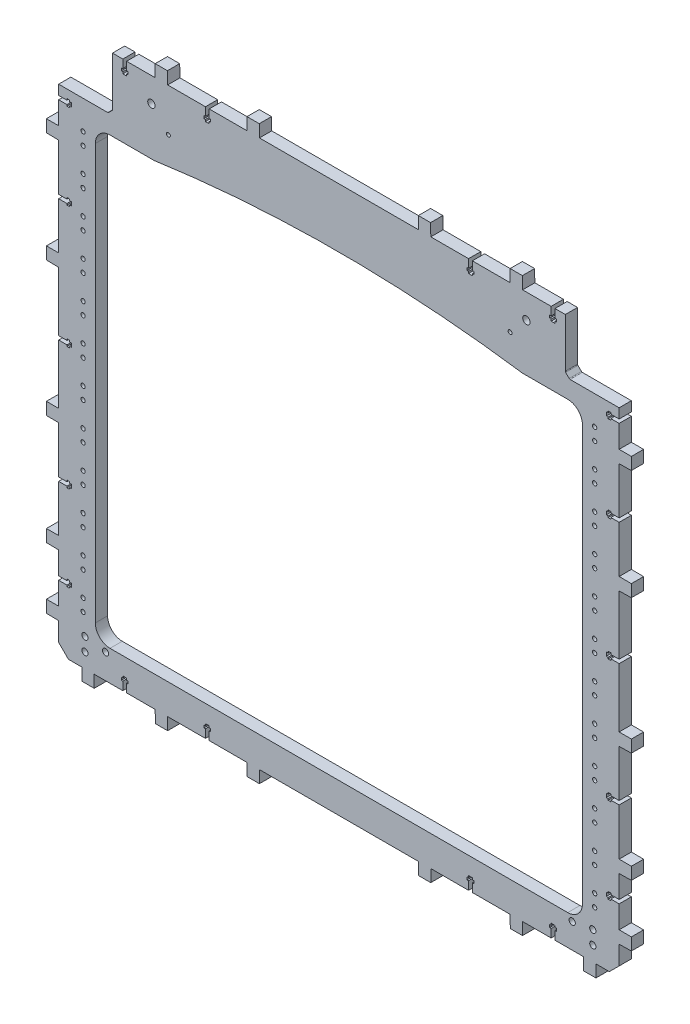
SolidWorks part; units mm, degrees
ref_plane "Front" through (0, 0, 0) normal (0, 0, 1) x (1, 0, 0)
ref_plane "Top" through (0, 0, 0) normal (0, 1, 0) x (1, 0, 0)
ref_plane "Right" through (0, 0, 0) normal (1, 0, 0) x (0, 0, -1)
sketch "Эскиз1" plane through (0, 0, 0) normal (0, 0, 1) x (1, 0, 0)
  line L0 (-199, -186.7207) -> (-199, 152.5)
  line L1 (109.05, 213) -> (105.95, 213)
  line L2 (186.9993, -198.7207) -> (-187, -198.7207)
  line L3 (199, 152.5) -> (198.9993, -186.7207)
  line L4 (109.05, 214.5) -> (109.05, 213)
  line L5 (110.25, 214.5) -> (109.05, 214.5)
  line L6 (110.25, 216.7) -> (110.25, 214.5)
  line L7 (109.05, 216.7) -> (110.25, 216.7)
  line L8 (109.05, 223.5) -> (109.05, 216.7)
  line L9 (139.9, 223.5) -> (109.05, 223.5)
  line L10 (139.9334, 233.4986) -> (139.9, 223.5)
  line L11 (149.9334, 233.4986) -> (139.9334, 233.4986)
  line L12 (150.1, 223.5) -> (149.9334, 233.4986)
  line L13 (173.45, 223.5) -> (150.1, 223.5)
  line L14 (173.45, 216.7) -> (173.45, 223.5)
  line L15 (172.25, 216.7) -> (173.45, 216.7)
  line L16 (172.25, 214.5) -> (172.25, 216.7)
  line L17 (173.45, 214.5) -> (172.25, 214.5)
  line L18 (173.45, 213) -> (173.45, 214.5)
  line L19 (176.55, 213) -> (173.45, 213)
  line L20 (176.55, 214.5) -> (176.55, 213)
  line L21 (177.75, 214.5) -> (176.55, 214.5)
  line L22 (177.75, 216.7) -> (177.75, 214.5)
  line L23 (176.55, 216.7) -> (177.75, 216.7)
  line L24 (176.55, 223.5) -> (176.55, 216.7)
  line L25 (185, 223.5) -> (176.55, 223.5)
  line L26 (229, 171.55) -> (229, 179.5)
  line L27 (222.2, 171.55) -> (229, 171.55)
  line L28 (222.2, 172.75) -> (222.2, 171.55)
  line L29 (220, 172.75) -> (222.2, 172.75)
  line L30 (220, 171.55) -> (220, 172.75)
  line L31 (218.5, 171.55) -> (220, 171.55)
  line L32 (218.5, 168.45) -> (218.5, 171.55)
  line L33 (220, 168.45) -> (218.5, 168.45)
  line L34 (220, 167.25) -> (220, 168.45)
  line L35 (222.2, 167.25) -> (220, 167.25)
  line L36 (222.2, 168.45) -> (222.2, 167.25)
  line L37 (229, 168.45) -> (222.2, 168.45)
  line L38 (229, 150.1) -> (229, 168.45)
  line L39 (238.9986, 150.0666) -> (229, 150.1)
  line L40 (238.9986, 140.0666) -> (238.9986, 150.0666)
  line L41 (229, 139.9) -> (238.9986, 140.0666)
  line L42 (229, 101.55) -> (229, 139.9)
  line L43 (222.2, 101.55) -> (229, 101.55)
  line L44 (222.2, 102.75) -> (222.2, 101.55)
  line L45 (220, 102.75) -> (222.2, 102.75)
  line L46 (220, 101.55) -> (220, 102.75)
  line L47 (218.5, 101.55) -> (220, 101.55)
  line L48 (218.5, 98.45) -> (218.5, 101.55)
  line L49 (220, 98.45) -> (218.5, 98.45)
  line L50 (220, 97.25) -> (220, 98.45)
  line L51 (222.2, 97.25) -> (220, 97.25)
  line L52 (222.2, 98.45) -> (222.2, 97.25)
  line L53 (229, 98.45) -> (222.2, 98.45)
  line L54 (229, 60.1) -> (229, 98.45)
  line L55 (238.9986, 60.0666) -> (229, 60.1)
  line L56 (238.9986, 50.0666) -> (238.9986, 60.0666)
  line L57 (229, 49.9) -> (238.9986, 50.0666)
  line L58 (238.9986, -49.9334) -> (229, -49.9)
  line L59 (238.9986, -59.9334) -> (238.9986, -49.9334)
  line L60 (229, -60.1) -> (238.9986, -59.9334)
  line L61 (229, -98.45) -> (229, -60.1)
  line L62 (222.2, -98.45) -> (229, -98.45)
  line L63 (222.2, -97.25) -> (222.2, -98.45)
  line L64 (220, -97.25) -> (222.2, -97.25)
  line L65 (220, -98.45) -> (220, -97.25)
  line L66 (218.5, -98.45) -> (220, -98.45)
  line L67 (218.5, -101.55) -> (218.5, -98.45)
  line L68 (220, -101.55) -> (218.5, -101.55)
  line L69 (220, -102.75) -> (220, -101.55)
  line L70 (222.2, -102.75) -> (220, -102.75)
  line L71 (222.2, -101.55) -> (222.2, -102.75)
  line L72 (229, -101.55) -> (222.2, -101.55)
  line L73 (229, -139.9) -> (229, -101.55)
  line L74 (238.9986, -139.9334) -> (229, -139.9)
  line L75 (238.9986, -149.9334) -> (238.9986, -139.9334)
  line L76 (229, -150.1) -> (238.9986, -149.9334)
  line L77 (229, -168.45) -> (229, -150.1)
  line L78 (222.2, -168.45) -> (229, -168.45)
  line L79 (222.2, -167.25) -> (222.2, -168.45)
  line L80 (220, -167.25) -> (222.2, -167.25)
  line L81 (220, -168.45) -> (220, -167.25)
  line L82 (218.5, -168.45) -> (220, -168.45)
  line L83 (218.5, -171.55) -> (218.5, -168.45)
  line L84 (220, -171.55) -> (218.5, -171.55)
  line L85 (220, -172.75) -> (220, -171.55)
  line L86 (222.2, -172.75) -> (220, -172.75)
  line L87 (222.2, -171.55) -> (222.2, -172.75)
  line L88 (229, -171.55) -> (222.2, -171.55)
  line L89 (229, -189.9) -> (229, -171.55)
  line L90 (238.9986, -189.9334) -> (229, -189.9)
  line L91 (238.9986, -199.9334) -> (238.9986, -189.9334)
  line L92 (229, -200.1) -> (238.9986, -199.9334)
  line L93 (229, -215.5) -> (229, -200.1)
  line L94 (221, -223.5) -> (229, -215.5)
  line L95 (210.1, -223.5) -> (221, -223.5)
  line L96 (210.0286, -233.4986) -> (210.1, -223.5)
  line L97 (200.0666, -233.4986) -> (210.0286, -233.4986)
  line L98 (199.9, -223.5) -> (200.0666, -233.4986)
  line L99 (176.55, -223.5) -> (199.9, -223.5)
  line L100 (176.55, -216.7) -> (176.55, -223.5)
  line L101 (177.75, -216.7) -> (176.55, -216.7)
  line L102 (177.75, -214.5) -> (177.75, -216.7)
  line L103 (176.55, -214.5) -> (177.75, -214.5)
  line L104 (176.55, -213) -> (176.55, -214.5)
  line L105 (173.45, -213) -> (176.55, -213)
  line L106 (173.45, -214.5) -> (173.45, -213)
  line L107 (172.25, -214.5) -> (173.45, -214.5)
  line L108 (172.25, -216.7) -> (172.25, -214.5)
  line L109 (173.45, -216.7) -> (172.25, -216.7)
  line L110 (173.45, -223.5) -> (173.45, -216.7)
  line L111 (150.1, -223.5) -> (173.45, -223.5)
  line L112 (150.0286, -233.4986) -> (150.1, -223.5)
  line L113 (140.0666, -233.4986) -> (150.0286, -233.4986)
  line L114 (139.9, -223.5) -> (140.0666, -233.4986)
  line L115 (109.05, -223.5) -> (139.9, -223.5)
  line L116 (109.05, -216.7) -> (109.05, -223.5)
  line L117 (110.25, -216.7) -> (109.05, -216.7)
  line L118 (110.25, -214.5) -> (110.25, -216.7)
  line L119 (109.05, -214.5) -> (110.25, -214.5)
  line L120 (109.05, -213) -> (109.05, -214.5)
  line L121 (105.95, -213) -> (109.05, -213)
  line L122 (105.95, -214.5) -> (105.95, -213)
  line L123 (104.75, -214.5) -> (105.95, -214.5)
  line L124 (104.75, -216.7) -> (104.75, -214.5)
  line L125 (105.95, -216.7) -> (104.75, -216.7)
  line L126 (105.95, -223.5) -> (105.95, -216.7)
  line L127 (75.1, -223.5) -> (105.95, -223.5)
  line L128 (75.0666, -233.4986) -> (75.1, -223.5)
  line L129 (65.0666, -233.4986) -> (75.0666, -233.4986)
  line L130 (64.9, -223.5) -> (65.0666, -233.4986)
  line L131 (-64.9, -223.5) -> (64.9, -223.5)
  line L132 (-64.9334, -233.4986) -> (-64.9, -223.5)
  line L133 (-74.9334, -233.4986) -> (-64.9334, -233.4986)
  line L134 (-75.1, -223.5) -> (-74.9334, -233.4986)
  line L135 (-105.95, -223.5) -> (-75.1, -223.5)
  line L136 (-105.95, -216.7) -> (-105.95, -223.5)
  line L137 (-104.75, -216.7) -> (-105.95, -216.7)
  line L138 (-104.75, -214.5) -> (-104.75, -216.7)
  line L139 (-105.95, -214.5) -> (-104.75, -214.5)
  line L140 (-105.95, -213) -> (-105.95, -214.5)
  line L141 (-109.05, -213) -> (-105.95, -213)
  line L142 (-109.05, -214.5) -> (-109.05, -213)
  line L143 (-110.25, -214.5) -> (-109.05, -214.5)
  line L144 (-110.25, -216.7) -> (-110.25, -214.5)
  line L145 (-109.05, -216.7) -> (-110.25, -216.7)
  line L146 (-109.05, -223.5) -> (-109.05, -216.7)
  line L147 (-139.9, -223.5) -> (-109.05, -223.5)
  line L148 (-139.9334, -233.4986) -> (-139.9, -223.5)
  line L149 (-149.9334, -233.4986) -> (-139.9334, -233.4986)
  line L150 (-150.1, -223.5) -> (-149.9334, -233.4986)
  line L151 (-173.45, -223.5) -> (-150.1, -223.5)
  line L152 (-173.45, -216.7) -> (-173.45, -223.5)
  line L153 (-172.25, -216.7) -> (-173.45, -216.7)
  line L154 (-172.25, -214.5) -> (-172.25, -216.7)
  line L155 (-173.45, -214.5) -> (-172.25, -214.5)
  line L156 (-173.45, -213) -> (-173.45, -214.5)
  line L157 (-176.55, -213) -> (-173.45, -213)
  line L158 (-176.55, -214.5) -> (-176.55, -213)
  line L159 (-177.75, -214.5) -> (-176.55, -214.5)
  line L160 (-177.75, -216.7) -> (-177.75, -214.5)
  line L161 (-176.55, -216.7) -> (-177.75, -216.7)
  line L162 (-176.55, -223.5) -> (-176.55, -216.7)
  line L163 (-199.9, -223.5) -> (-176.55, -223.5)
  line L164 (-199.9334, -233.4986) -> (-199.9, -223.5)
  line L165 (-209.9334, -233.4986) -> (-199.9334, -233.4986)
  line L166 (-210.1, -223.5) -> (-209.9334, -233.4986)
  line L167 (-221, -223.5) -> (-210.1, -223.5)
  line L168 (-229, -215.5) -> (-221, -223.5)
  line L169 (-229, -200.1) -> (-229, -215.5)
  line L170 (-238.9986, -199.9334) -> (-229, -200.1)
  line L171 (-238.9986, -189.9334) -> (-238.9986, -199.9334)
  line L172 (-229, -189.9) -> (-238.9986, -189.9334)
  line L173 (-229, -171.55) -> (-229, -189.9)
  line L174 (-222.2, -171.55) -> (-229, -171.55)
  line L175 (-222.2, -172.75) -> (-222.2, -171.55)
  line L176 (-220, -172.75) -> (-222.2, -172.75)
  line L177 (-220, -171.55) -> (-220, -172.75)
  line L178 (-218.5, -171.55) -> (-220, -171.55)
  line L179 (-218.5, -168.45) -> (-218.5, -171.55)
  line L180 (-220, -168.45) -> (-218.5, -168.45)
  line L181 (-220, -167.25) -> (-220, -168.45)
  line L182 (-222.2, -167.25) -> (-220, -167.25)
  line L183 (-222.2, -168.45) -> (-222.2, -167.25)
  line L184 (-229, -168.45) -> (-222.2, -168.45)
  line L185 (-229, -150.1) -> (-229, -168.45)
  line L186 (-238.9986, -149.9334) -> (-229, -150.1)
  line L187 (-238.9986, -139.9334) -> (-238.9986, -149.9334)
  line L188 (-229, -139.9) -> (-238.9986, -139.9334)
  line L189 (-229, -101.55) -> (-229, -139.9)
  line L190 (-222.2, -101.55) -> (-229, -101.55)
  line L191 (-222.2, -102.75) -> (-222.2, -101.55)
  line L192 (-220, -102.75) -> (-222.2, -102.75)
  line L193 (-220, -101.55) -> (-220, -102.75)
  line L194 (-218.5, -101.55) -> (-220, -101.55)
  line L195 (-218.5, -98.45) -> (-218.5, -101.55)
  line L196 (-220, -98.45) -> (-218.5, -98.45)
  line L197 (-220, -97.25) -> (-220, -98.45)
  line L198 (-222.2, -97.25) -> (-220, -97.25)
  line L199 (-222.2, -98.45) -> (-222.2, -97.25)
  line L200 (-229, -98.45) -> (-222.2, -98.45)
  line L201 (-229, -60.1) -> (-229, -98.45)
  line L202 (-238.9986, -59.9334) -> (-229, -60.1)
  line L203 (-238.9986, -49.9334) -> (-238.9986, -59.9334)
  line L204 (-229, -49.9) -> (-238.9986, -49.9334)
  line L205 (-238.9986, 50.0666) -> (-229, 49.9)
  line L206 (-238.9986, 60.0666) -> (-238.9986, 50.0666)
  line L207 (-229, 60.1) -> (-238.9986, 60.0666)
  line L208 (-229, 98.45) -> (-229, 60.1)
  line L209 (-222.2, 98.45) -> (-229, 98.45)
  line L210 (-222.2, 97.25) -> (-222.2, 98.45)
  line L211 (-220, 97.25) -> (-222.2, 97.25)
  line L212 (-220, 98.45) -> (-220, 97.25)
  line L213 (-218.5, 98.45) -> (-220, 98.45)
  line L214 (-218.5, 101.55) -> (-218.5, 98.45)
  line L215 (-220, 101.55) -> (-218.5, 101.55)
  line L216 (-220, 102.75) -> (-220, 101.55)
  line L217 (-222.2, 102.75) -> (-220, 102.75)
  line L218 (-222.2, 101.55) -> (-222.2, 102.75)
  line L219 (-229, 101.55) -> (-222.2, 101.55)
  line L220 (-229, 139.9) -> (-229, 101.55)
  line L221 (-238.9986, 140.0666) -> (-229, 139.9)
  line L222 (-238.9986, 150.0666) -> (-238.9986, 140.0666)
  line L223 (-229, 150.1) -> (-238.9986, 150.0666)
  line L224 (-229, 168.45) -> (-229, 150.1)
  line L225 (-222.2, 168.45) -> (-229, 168.45)
  line L226 (-222.2, 167.25) -> (-222.2, 168.45)
  line L227 (-220, 167.25) -> (-222.2, 167.25)
  line L228 (-220, 168.45) -> (-220, 167.25)
  line L229 (-218.5, 168.45) -> (-220, 168.45)
  line L230 (-218.5, 171.55) -> (-218.5, 168.45)
  line L231 (-220, 171.55) -> (-218.5, 171.55)
  line L232 (-220, 172.75) -> (-220, 171.55)
  line L233 (-222.2, 172.75) -> (-220, 172.75)
  line L234 (-222.2, 171.55) -> (-222.2, 172.75)
  line L235 (-229, 171.55) -> (-222.2, 171.55)
  line L236 (-229, 179.5) -> (-229, 171.55)
  line L237 (-176.55, 223.5) -> (-185, 223.5)
  line L238 (-176.55, 216.7) -> (-176.55, 223.5)
  line L239 (-177.75, 216.7) -> (-176.55, 216.7)
  line L240 (-177.75, 214.5) -> (-177.75, 216.7)
  line L241 (-176.55, 214.5) -> (-177.75, 214.5)
  line L242 (-176.55, 213) -> (-176.55, 214.5)
  line L243 (-173.45, 213) -> (-176.55, 213)
  line L244 (-173.45, 214.5) -> (-173.45, 213)
  line L245 (-172.25, 214.5) -> (-173.45, 214.5)
  line L246 (-172.25, 216.7) -> (-172.25, 214.5)
  line L247 (-173.45, 216.7) -> (-172.25, 216.7)
  line L248 (-173.45, 223.5) -> (-173.45, 216.7)
  line L249 (-150.1, 223.5) -> (-173.45, 223.5)
  line L250 (-150.0666, 233.4986) -> (-150.1, 223.5)
  line L251 (-140.0666, 233.4986) -> (-150.0666, 233.4986)
  line L252 (-139.9, 223.5) -> (-140.0666, 233.4986)
  line L253 (-109.05, 223.5) -> (-139.9, 223.5)
  line L254 (-109.05, 216.7) -> (-109.05, 223.5)
  line L255 (-110.25, 216.7) -> (-109.05, 216.7)
  line L256 (-110.25, 214.5) -> (-110.25, 216.7)
  line L257 (-109.05, 214.5) -> (-110.25, 214.5)
  line L258 (-109.05, 213) -> (-109.05, 214.5)
  line L259 (-105.95, 213) -> (-109.05, 213)
  line L260 (-105.95, 214.5) -> (-105.95, 213)
  line L261 (-104.75, 214.5) -> (-105.95, 214.5)
  line L262 (-104.75, 216.7) -> (-104.75, 214.5)
  line L263 (-105.95, 216.7) -> (-104.75, 216.7)
  line L264 (-105.95, 223.5) -> (-105.95, 216.7)
  line L265 (-75.1, 223.5) -> (-105.95, 223.5)
  line L266 (-75.0666, 233.4986) -> (-75.1, 223.5)
  line L267 (-65.0666, 233.4986) -> (-75.0666, 233.4986)
  line L268 (-64.9, 223.5) -> (-65.0666, 233.4986)
  line L269 (64.9, 223.5) -> (-64.9, 223.5)
  line L270 (64.9334, 233.4986) -> (64.9, 223.5)
  line L271 (74.9334, 233.4986) -> (64.9334, 233.4986)
  line L272 (75.1, 223.5) -> (74.9334, 233.4986)
  line L273 (105.95, 223.5) -> (75.1, 223.5)
  line L274 (105.95, 216.7) -> (105.95, 223.5)
  line L275 (104.75, 216.7) -> (105.95, 216.7)
  line L276 (104.75, 214.5) -> (104.75, 216.7)
  line L277 (105.95, 214.5) -> (104.75, 214.5)
  line L278 (105.95, 213) -> (105.95, 214.5)
  line L279 (187, 164.5) -> (150.1, 164.5)
  line L280 (-187, 164.5) -> (-151.0167, 164.5)
  line L281 (188.9142, 179.5) -> (229, 179.5)
  line L282 (185, 183.4142) -> (185, 223.5)
  line L283 (-188.9142, 179.5) -> (-229, 179.5)
  line L284 (-185, 183.4142) -> (-185, 223.5)
  line L285 (-188.2071, 179.7929) -> (-185.2929, 182.7071)
  line L286 (185.2929, 182.7071) -> (188.2071, 179.7929)
  line L287 (-222.2, -1.55) -> (-229, -1.55)
  line L288 (-222.2, -2.75) -> (-222.2, -1.55)
  line L289 (-220, -2.75) -> (-222.2, -2.75)
  line L290 (-220, -1.55) -> (-220, -2.75)
  line L291 (-218.5, -1.55) -> (-220, -1.55)
  line L292 (-218.5, 1.55) -> (-218.5, -1.55)
  line L293 (-220, 1.55) -> (-218.5, 1.55)
  line L294 (-220, 2.75) -> (-220, 1.55)
  line L295 (-222.2, 2.75) -> (-220, 2.75)
  line L296 (-222.2, 1.55) -> (-222.2, 2.75)
  line L297 (-229, 1.55) -> (-222.2, 1.55)
  line L298 (222.2, 1.55) -> (229, 1.55)
  line L299 (222.2, 2.75) -> (222.2, 1.55)
  line L300 (220, 2.75) -> (222.2, 2.75)
  line L301 (220, 1.55) -> (220, 2.75)
  line L302 (218.5, 1.55) -> (220, 1.55)
  line L303 (218.5, -1.55) -> (218.5, 1.55)
  line L304 (220, -1.55) -> (218.5, -1.55)
  line L305 (220, -2.75) -> (220, -1.55)
  line L306 (222.2, -2.75) -> (220, -2.75)
  line L307 (222.2, -1.55) -> (222.2, -2.75)
  line L308 (229, -1.55) -> (222.2, -1.55)
  line L309 (-229, 49.9) -> (-229, 1.55)
  line L310 (-229, -1.55) -> (-229, -49.9)
  line L311 (229, 49.9) -> (229, 1.55)
  line L312 (229, -1.55) -> (229, -49.9)
  circle A0 centre (-209, 156) radius 1.75
  circle A1 centre (-209, 96) radius 1.75
  circle A2 centre (-209, 56) radius 1.75
  circle A3 centre (209, 56) radius 1.75
  circle A4 centre (209, 156) radius 1.75
  circle A5 centre (209, 116) radius 1.75
  circle A6 centre (209, -114) radius 1.75
  circle A7 centre (209, -154) radius 1.75
  circle A8 centre (-209, -94) radius 1.75
  circle A9 centre (-207.5, -200.5) radius 2.55
  circle A10 centre (207.5, -200.5) radius 2.55
  circle A11 centre (-209, -154) radius 1.75
  circle A12 centre (-209, -114) radius 1.75
  circle A13 centre (-209, 116) radius 1.75
  circle A14 centre (209, -94) radius 1.75
  circle A15 centre (209, 96) radius 1.75
  circle A16 centre (209, 36) radius 1.75
  circle A17 centre (-209, 36) radius 1.75
  arc A18 (-199, -186.7207) -> (-187, -198.7207) centre (-187, -186.7207) ccw
  arc A19 (186.9993, -198.7207) -> (198.9993, -186.7207) centre (186.9993, -186.7207) ccw
  arc A20 (199, 152.5) -> (187, 164.5) centre (187, 152.5) ccw
  arc A21 (-187, 164.5) -> (-199, 152.5) centre (-187, 152.5) ccw
  circle A24 centre (207.5, -211.5) radius 2.55
  circle A25 centre (190.6472, -203.2105) radius 2.55
  circle A26 centre (-207.5, -211.5) radius 2.55
  circle A27 centre (-190.65, -203.2105) radius 2.55
  circle A28 centre (209, -184) radius 1.75
  circle A29 centre (-209, -184) radius 1.75
  circle A30 centre (-209, 66) radius 1.75
  circle A31 centre (-209, 146) radius 1.75
  circle A32 centre (-209, 86) radius 1.75
  circle A33 centre (-209, -84) radius 1.75
  circle A34 centre (-209, -124) radius 1.75
  circle A35 centre (-209, -144) radius 1.75
  circle A36 centre (-209, 26) radius 1.75
  circle A37 centre (-209, 126) radius 1.75
  circle A38 centre (-209, -174) radius 1.75
  circle A39 centre (209, 66) radius 1.75
  circle A40 centre (209, 126) radius 1.75
  circle A41 centre (209, 86) radius 1.75
  circle A42 centre (209, -144) radius 1.75
  circle A43 centre (209, -124) radius 1.75
  circle A44 centre (209, -84) radius 1.75
  circle A45 centre (209, 146) radius 1.75
  circle A46 centre (209, 26) radius 1.75
  circle A47 centre (209, -174) radius 1.75
  arc A48 (150.1, 164.5) -> (-151.0167, 164.5) centre (-0.4583, -888.4435) ccw
  arc A49 (185, 183.4142) -> (185.2929, 182.7071) centre (186, 183.4142) ccw
  arc A50 (188.2071, 179.7929) -> (188.9142, 179.5) centre (188.9142, 180.5) ccw
  arc A51 (-188.9142, 179.5) -> (-188.2071, 179.7929) centre (-188.9142, 180.5) ccw
  arc A52 (-185.2929, 182.7071) -> (-185, 183.4142) centre (-186, 183.4142) ccw
  circle A55 centre (209, -4) radius 1.75
  circle A56 centre (209, -24) radius 1.75
  circle A57 centre (209, 6) radius 1.75
  circle A58 centre (209, -34) radius 1.75
  circle A59 centre (-209, -4) radius 1.75
  circle A60 centre (-209, -24) radius 1.75
  circle A61 centre (-209, 6) radius 1.75
  circle A62 centre (-209, -34) radius 1.75
  circle A63 centre (-209, -54) radius 1.75
  circle A64 centre (-209, -64) radius 1.75
  circle A65 centre (209, -54) radius 1.75
  circle A66 centre (209, -64) radius 1.75
  circle A67 centre (-153.2, 203.6) radius 3
  circle A68 centre (153.2, 203.6) radius 3
  circle A69 centre (-139.3167, 188.5049) radius 1.6
  circle A70 centre (139.9, 188.5) radius 1.6
  dimension "D1" = 10
  dimension "D2" = 59
  dimension "D3" = 59
extrude "Бобышка-Вытянуть1" add sketch "Эскиз1" along normal blind 10
